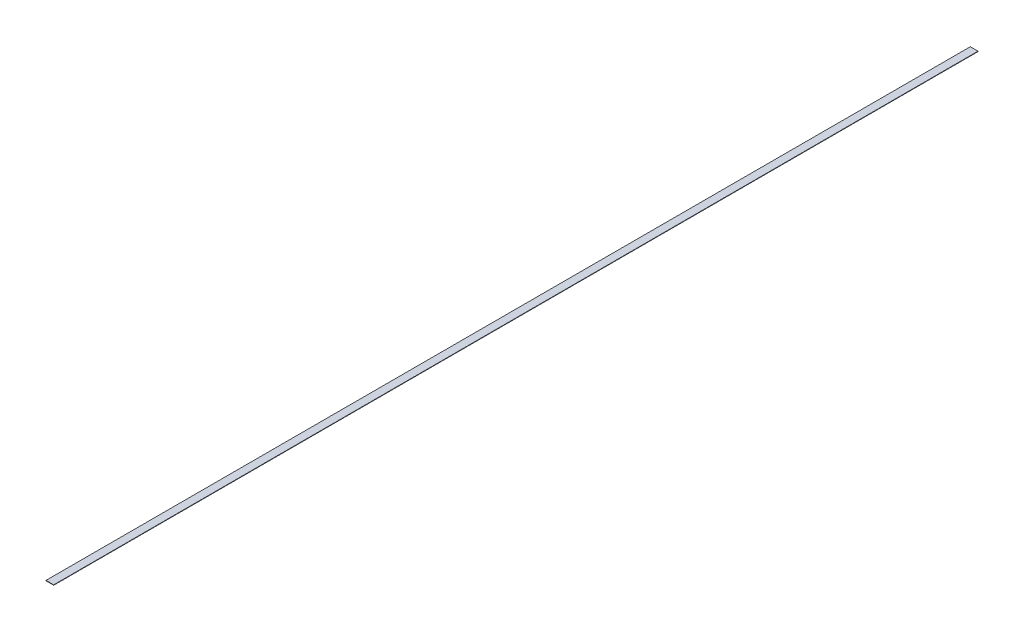
SolidWorks part; units mm, degrees
ref_plane "Front Plane" through (0, 0, 0) normal (0, 0, 1) x (1, 0, 0)
ref_plane "Top Plane" through (0, 0, 0) normal (0, 1, 0) x (1, 0, 0)
ref_plane "Right Plane" through (0, 0, 0) normal (1, 0, 0) x (0, 0, -1)
sketch "Sketch1" plane through (0, 0, 0) normal (0, 0, 1) x (1, 0, 0)
  line L0 (6505.0765, 4620.0146) -> (6505.0765, 4619.3288)
  line L1 (6517.7765, 4620.0146) -> (6517.7765, 4619.3288)
  line L2 (6517.7765, 4619.3288) -> (6505.0765, 4619.3288)
  line L3 (6517.7765, 4620.0146) -> (6505.0765, 4620.0146)
extrude "Boss-Extrude1" add sketch "Sketch1" along normal blind 1524
